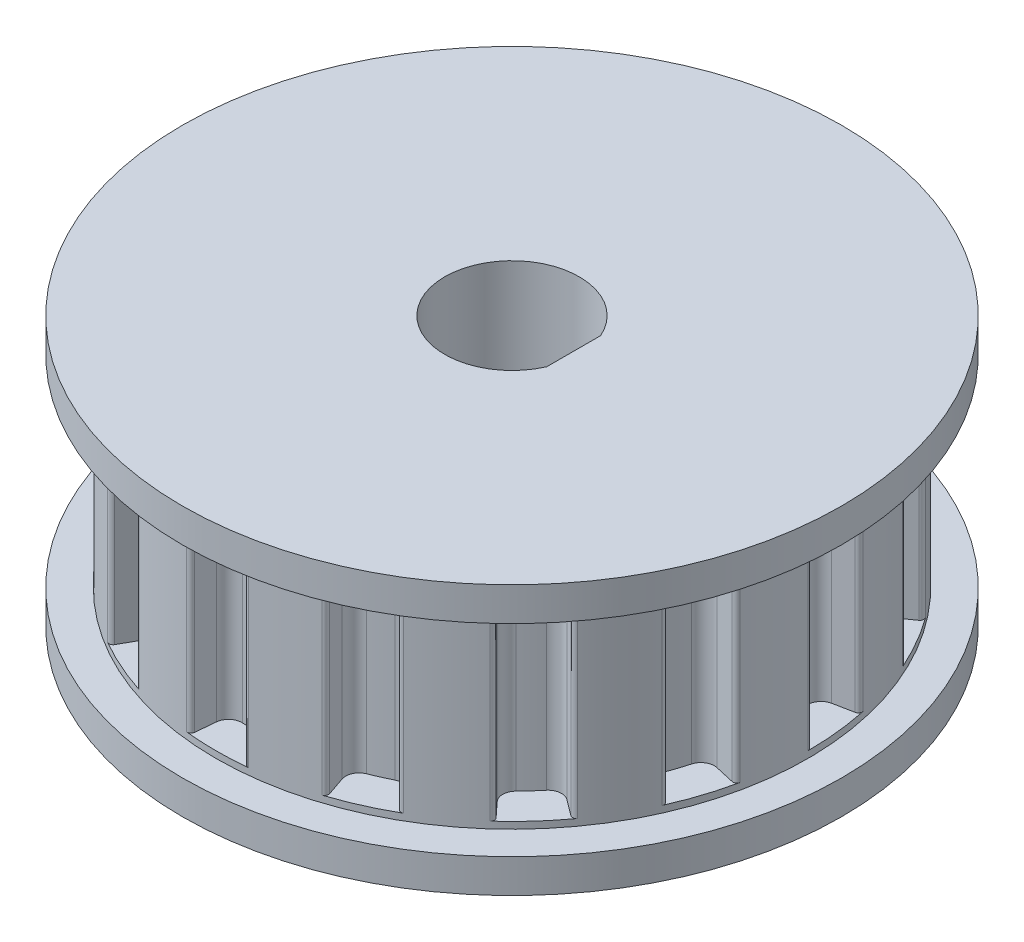
SolidWorks part; units mm, degrees
material "ABS"
ref_plane "Front Plane" through (0, 0, 0) normal (0, 0, 1) x (1, 0, 0)
ref_plane "Top Plane" through (0, 0, 0) normal (0, 1, 0) x (1, 0, 0)
ref_plane "Right Plane" through (0, 0, 0) normal (1, 0, 0) x (0, 0, -1)
sketch "Sketch4" plane through (0, 0, 0) normal (1, 0, 0) x (0, 0, -1)
  line L0 (0, -5) -> (12.25, -5)
  line L1 (12.25, -5) -> (12.25, -3.75)
  line L2 (12.25, -3.75) -> (11, -3.75)
  line L3 (11, -3.75) -> (11, 3.75)
  line L4 (11, 3.75) -> (12.25, 3.75)
  line L5 (12.25, 3.75) -> (12.25, 5)
  line L6 (12.25, 5) -> (0, 5)
  line L7 (0, 5) -> (0, -5)
  point P3 (0, 0)
  point P11 (0, 0)
  point P12 (0, 0)
  point P13 (-1.1802, -1.0734)
  dimension "D1" = 7.5
  dimension "D2" = 10
  dimension "D3" = 1.25
  dimension "D4" = 11
revolve "Revolve1" add sketch "Sketch4" angle 360 about L7
sketch "Sketch5" plane through (0, 0, 0) normal (0, 1, 0) x (1, 0, 0)
  line L0 (0.9986, -10.9546) -> (0.8733, -9.5803)
  line L1 (-0.8733, -9.5803) -> (-0.9986, -10.9546)
  circle A0 centre (0, 0) radius 11 construction
  arc A3 (0.8733, -9.5803) -> (-0.8733, -9.5803) centre (0, 0) cw
  arc A4 (0.9986, -10.9546) -> (-0.9986, -10.9546) centre (0, 0) cw
  point P8 (0, -11)
  point P10 (0, -9.62)
  dimension "D2" = 2
  dimension "D1" = 1.38
extrude "Cut-Extrude2" cut sketch "Sketch5" against normal mid plane 7
fillet "Fillet1" radius 0.15 2 edges at (0.9986, 0, 10.9546) (-0.9986, 0, 10.9546)
fillet "Fillet4" radius 0.5 2 edges at (-0.8733, 0, 9.5803) (0.8733, 0, 9.5803)
pattern_circular "CirPattern1" count 15 over 360 about axis through (0, 0, 0) along (0, 1, 0) of "Cut-Extrude2", "Fillet4", "Fillet1"
sketch "Sketch6" plane through (0, 5, 0) normal (0, 1, 0) x (1, 0, 0)
  line L0 (2.2913, 1) -> (2.2913, -1)
  arc A0 (2.2913, 1) -> (2.2913, -1) centre (0, 0) ccw
  dimension "D1" = 5
  dimension "D2" = 2
extrude "Cut-Extrude3" cut sketch "Sketch6" against normal through all
